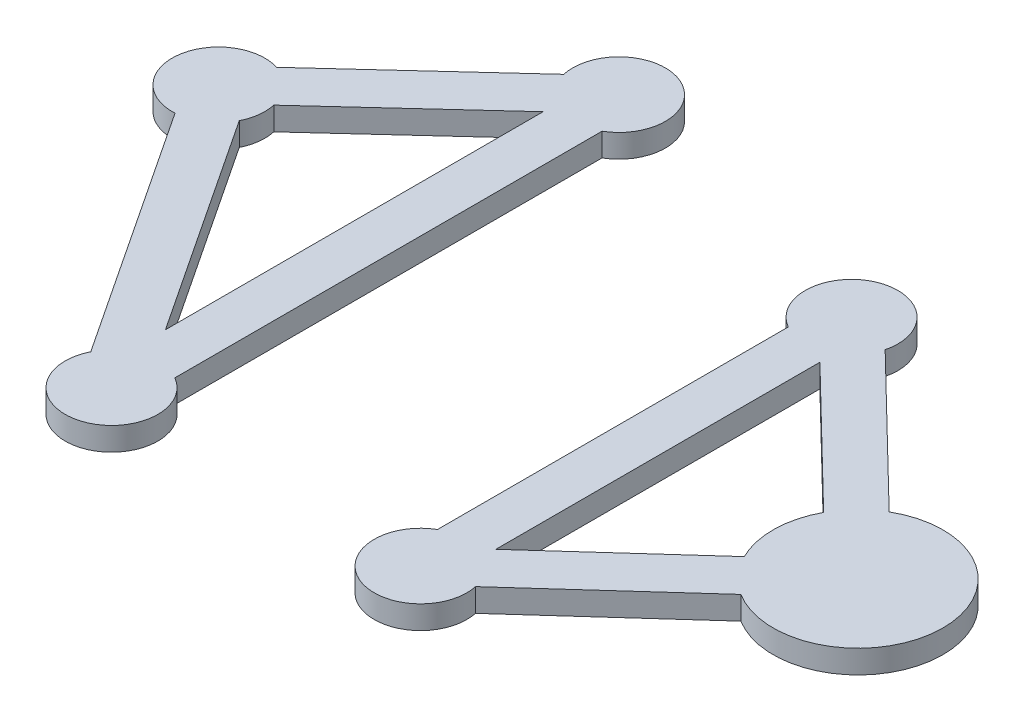
SolidWorks part; units mm, degrees
ref_plane "Спереди" through (0, 0, 0) normal (0, 0, 1) x (1, 0, 0)
ref_plane "Сверху" through (0, 0, 0) normal (0, 1, 0) x (1, 0, 0)
ref_plane "Справа" through (0, 0, 0) normal (1, 0, 0) x (0, 0, -1)
other "Configuration Table"
sketch "Эскиз1" plane through (0, 0, 0) normal (0, 1, 0) x (1, 0, 0)
  line L0 (-67.0272, 40.8721) -> (-40, 0) construction
  line L1 (-40, 0) -> (-40, 65.7) construction
  line L2 (-40, 65.7) -> (-67.0272, 40.8721) construction
  line L3 (0, 55.8) -> (29.7602, 26.8763) construction
  line L4 (29.7602, 26.8763) -> (0, 0) construction
  line L5 (0, 55.8) -> (0, 0) construction
  line L6 (0, 0) -> (-40, 0) construction
  line L8 (-66.5152, 34.659) -> (-44.2247, 0.9499) construction
  line L11 (-47.865, 17.333) -> (-25.5745, -16.3761) construction
  line L12 (-37, 40.8721) -> (-37, 25.5534) construction
  line L14 (-43, 45.1596) -> (-43, 29.8408) construction
  line L15 (-59.2829, 52.06) -> (-52.3912, 58.3908) construction
  line L17 (-54.2851, 48.5036) -> (-47.3934, 54.8345) construction
  line L18 (-65.2301, 46.5967) -> (-45.8562, 64.3941)
  line L20 (-37, 60.5038) -> (-37, 5.1962)
  line L22 (-66.6635, 34.8832) -> (-45.3684, 2.6795)
  line L32 (-61.171, 42.1781) -> (-43, 58.8704)
  line L33 (-43, 58.8704) -> (-43, 9.9758)
  line L34 (-43, 9.9758) -> (-61.6587, 38.1926)
  line L36 (-3, 38.1926) -> (-3, 20.958) construction
  line L38 (3, 19.403) -> (3, 2.1683) construction
  line L39 (9.9396, 50.3232) -> (19.7611, 40.7779) construction
  line L41 (8.7772, 43.0861) -> (17.7954, 34.3214) construction
  line L43 (9.49, 12.6127) -> (16.4921, 18.9362) construction
  line L45 (11.918, 6.7208) -> (20.2311, 14.2283) construction
  line L46 (19.8954, 22.0097) -> (3, 6.7516)
  line L53 (3, 6.7516) -> (3, 48.7009)
  line L55 (3, 48.7009) -> (20.0802, 32.1009)
  line L57 (-3, 50.6038) -> (-3, 5.1962)
  line L58 (5.867, 1.2562) -> (23.9168, 17.5568)
  line L59 (5.8171, 54.3299) -> (24.2619, 36.4036)
  circle A14 centre (-40, 65.7) radius 6 construction
  circle A15 centre (-67.0272, 40.8721) radius 6 construction
  circle A16 centre (-40, 0) radius 6 construction
  circle A17 centre (0, 0) radius 6 construction
  circle A18 centre (29.7602, 26.8763) radius 11 construction
  circle A19 centre (0, 55.8) radius 6 construction
  arc A20 (-66.6635, 34.8832) -> (-65.2301, 46.5967) centre (-67.0272, 40.8721) cw
  arc A21 (-45.8562, 64.3941) -> (-37, 60.5038) centre (-40, 65.7) cw
  arc A22 (-45.3684, 2.6795) -> (-37, 5.1962) centre (-40, 0) ccw
  arc A23 (-61.171, 42.1781) -> (-61.6587, 38.1926) centre (-67.0272, 40.8721) cw
  arc A24 (5.8171, 54.3299) -> (-3, 50.6038) centre (0, 55.8) ccw
  arc A25 (23.9168, 17.5568) -> (24.2619, 36.4036) centre (29.7602, 26.8763) ccw
  arc A26 (-3, 5.1962) -> (5.867, 1.2562) centre (0, 0) ccw
  arc A27 (20.0802, 32.1009) -> (19.8954, 22.0097) centre (29.7602, 26.8763) ccw
  dimension "D14" = 12
  dimension "D15" = 12
  dimension "D16" = 12
  dimension "D17" = 12
  dimension "D18" = 12
  dimension "D19" = 22
  dimension "D1" = 55.8
  dimension "D2" = 40.1
  dimension "D3" = 41.5
  dimension "D4" = 65.7
  dimension "D5" = 49
  dimension "D6" = 36.7
  dimension "D7" = 40
  dimension "D8" = 3
  dimension "D9" = 3
  dimension "D10" = 3
  dimension "D11" = 3
  dimension "D12" = 3
  dimension "D13" = 3
  dimension "D20" = 3
  dimension "D21" = 3
  dimension "D22" = 3
  dimension "D23" = 3
  dimension "D24" = 3
  dimension "D25" = 3
extrude "Бобышка-Вытянуть1" add sketch "Эскиз1" along normal blind 3
equation "\"A\" = 12мм"
equation "\"B\" = 22мм"
equation "\"w\"= 6мм"
equation "\"D8@Эскиз1\"=\"w\"/2"
equation "\"D9@Эскиз1\"=\"w\"/2"
equation "\"D10@Эскиз1\"=\"w\"/2"
equation "\"D11@Эскиз1\"=\"w\"/2"
equation "\"D12@Эскиз1\"=\"w\"/2"
equation "\"D13@Эскиз1\"=\"w\"/2"
equation "\"D14@Эскиз1\"=\"A\""
equation "\"D15@Эскиз1\"=\"A\""
equation "\"D16@Эскиз1\"=\"A\""
equation "\"D17@Эскиз1\"=\"A\""
equation "\"D18@Эскиз1\"=\"A\""
equation "\"D19@Эскиз1\"=\"B\""
equation "\"D20@Эскиз1\"=\"w\"/2"
equation "\"D21@Эскиз1\"=\"w\"/2"
equation "\"D22@Эскиз1\"=\"w\"/2"
equation "\"D23@Эскиз1\"=\"w\"/2"
equation "\"D24@Эскиз1\"=\"w\"/2"
equation "\"D25@Эскиз1\"=\"w\"/2"
